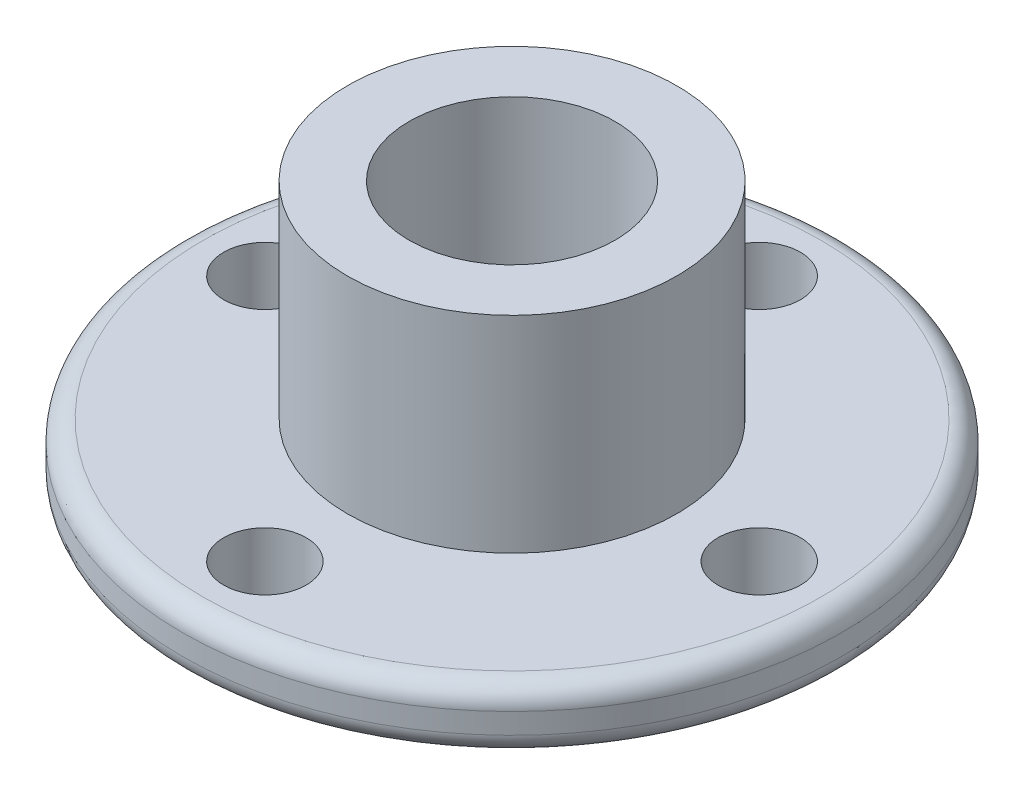
SolidWorks part; units mm, degrees
ref_plane "正面" through (0, 0, 0) normal (0, 0, 1) x (1, 0, 0)
ref_plane "平面" through (0, 0, 0) normal (0, 1, 0) x (1, 0, 0)
ref_plane "右側面" through (0, 0, 0) normal (1, 0, 0) x (0, 0, -1)
sketch "ｽｹｯﾁ1" plane through (0, 0, 0) normal (0, 1, 0) x (1, 0, 0)
  circle A0 centre (0, 0) radius 16
  dimension "D1" = 32
extrude "ﾎﾞｽ - 押し出し1" add sketch "ｽｹｯﾁ1" along normal blind 3
sketch "ｽｹｯﾁ2" plane through (0, 3, 0) normal (0, 1, 0) x (1, 0, 0)
  circle A0 centre (0, 0) radius 12 construction
  circle A1 centre (0, 12) radius 2
  circle A2 centre (12, 0) radius 2
  circle A3 centre (0, -12) radius 2
  circle A4 centre (-12, 0) radius 2
  circle A5 centre (0, 0) radius 5
  point P14 (0, 0)
  dimension "D1" = 24
  dimension "D2" = 4
  dimension "D4" = 10
  dimension "D3" = 4
extrude "ｶｯﾄ - 押し出し1" cut sketch "ｽｹｯﾁ2" against normal blind 3
sketch "ｽｹｯﾁ4" plane through (0, 3, 0) normal (0, 1, 0) x (1, 0, 0)
  circle A0 centre (0, 0) radius 8
  circle A1 centre (0, 0) radius 5 construction
  circle A2 centre (0, 0) radius 5
  dimension "D1" = 16
extrude "ﾎﾞｽ - 押し出し2" add sketch "ｽｹｯﾁ4" along normal blind 10
fillet "ﾌｨﾚｯﾄ1" radius 1 2 edges at (0, 0, 16) (0, 3, 16)
